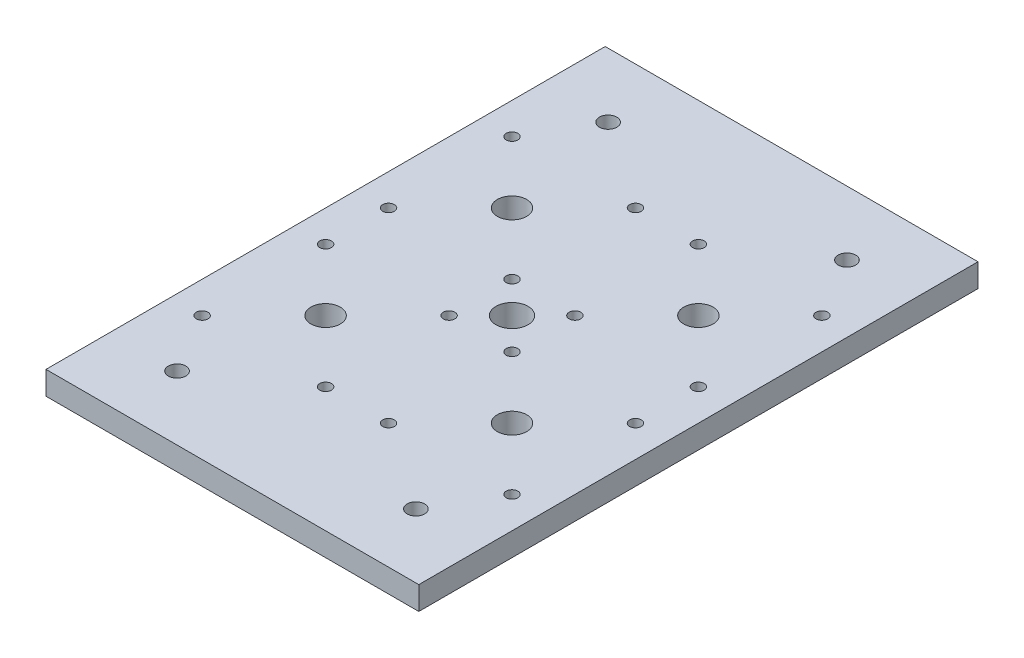
SolidWorks part; units mm, degrees
material "Beech"
ref_plane "Front Plane" through (0, 0, 0) normal (0, 0, 1) x (1, 0, 0)
ref_plane "Top Plane" through (0, 0, 0) normal (0, 1, 0) x (1, 0, 0)
ref_plane "Right Plane" through (0, 0, 0) normal (1, 0, 0) x (0, 0, -1)
sketch "Sketch1" plane through (0, 0, 0) normal (0, 1, 0) x (1, 0, 0)
  line L0 (0, 76.2) -> (0, 0) construction
  line L1 (-50.8, 76.2) -> (50.8, 76.2)
  line L2 (-50.8, 76.2) -> (-50.8, -76.2)
  line L3 (-50.8, -76.2) -> (50.8, -76.2)
  line L4 (50.8, 76.2) -> (50.8, -76.2)
  line L5 (0, 0) -> (-50.8, 0) construction
  line L6 (-21.4, 25.4) -> (-25.4, 25.4) construction
  line L7 (-45.4, 5.4) -> (-5.4, 5.4) construction
  line L8 (-45.4, 5.4) -> (-45.4, 45.4) construction
  line L9 (-45.4, 45.4) -> (-5.4, 45.4) construction
  line L10 (-5.4, 5.4) -> (-5.4, 45.4) construction
  line L11 (-45.4, 5.4) -> (-5.4, 45.4) construction
  line L12 (-45.4, 45.4) -> (-5.4, 5.4) construction
  line L13 (-25.4, 25.4) -> (-25.4, 62.7159) construction
  line L14 (-25.4, 62.7159) -> (-25.4, 25.4) construction
  line L15 (-25.4, 25.4) -> (-87.8323, 25.4) construction
  circle A0 centre (-25.4, 25.4) radius 4
  circle A1 centre (-42.225, 42.225) radius 1.5875
  circle A2 centre (-8.575, 42.225) radius 1.5875
  circle A3 centre (-8.575, 8.575) radius 1.5875
  circle A4 centre (-42.225, 8.575) radius 1.5875
  circle A5 centre (8.575, 8.575) radius 1.5875
  circle A6 centre (42.225, 8.575) radius 1.5875
  circle A7 centre (42.225, 42.225) radius 1.5875
  circle A8 centre (8.575, 42.225) radius 1.5875
  circle A9 centre (25.4, 25.4) radius 4
  circle A10 centre (42.225, -8.575) radius 1.5875
  circle A11 centre (42.225, -42.225) radius 1.5875
  circle A12 centre (8.575, -42.225) radius 1.5875
  circle A13 centre (25.4, -25.4) radius 4
  circle A14 centre (8.575, -8.575) radius 1.5875
  circle A15 centre (-8.575, -8.575) radius 1.5875
  circle A16 centre (-42.225, -8.575) radius 1.5875
  circle A17 centre (-8.575, -42.225) radius 1.5875
  circle A18 centre (-25.4, -25.4) radius 4
  circle A19 centre (-42.225, -42.225) radius 1.5875
  circle A20 centre (0, 0) radius 4.3656
  circle A21 centre (32.5437, 58.7375) radius 2.3812
  circle A22 centre (32.5438, -58.7375) radius 2.3812
  circle A23 centre (-32.5438, -58.7375) radius 2.3812
  circle A24 centre (-32.5437, 58.7375) radius 2.3812
  point P58 (32.5437, 64.9465)
  dimension "D3" = 8
  dimension "D7" = 3.175
  dimension "D10" = 8.7312
  dimension "D13" = 4.7625
  dimension "D1" = 101.6
  dimension "D2" = 152.4
  dimension "D4" = 40
  dimension "D5" = 40
  dimension "D6" = 3.175
  dimension "D8" = 50.8
  dimension "D9" = 50.8
  dimension "D11" = 33.65
  dimension "D12" = 18.2562
  dimension "D14" = 17.4625
extrude "Boss-Extrude1" add sketch "Sketch1" along normal blind 6.35
